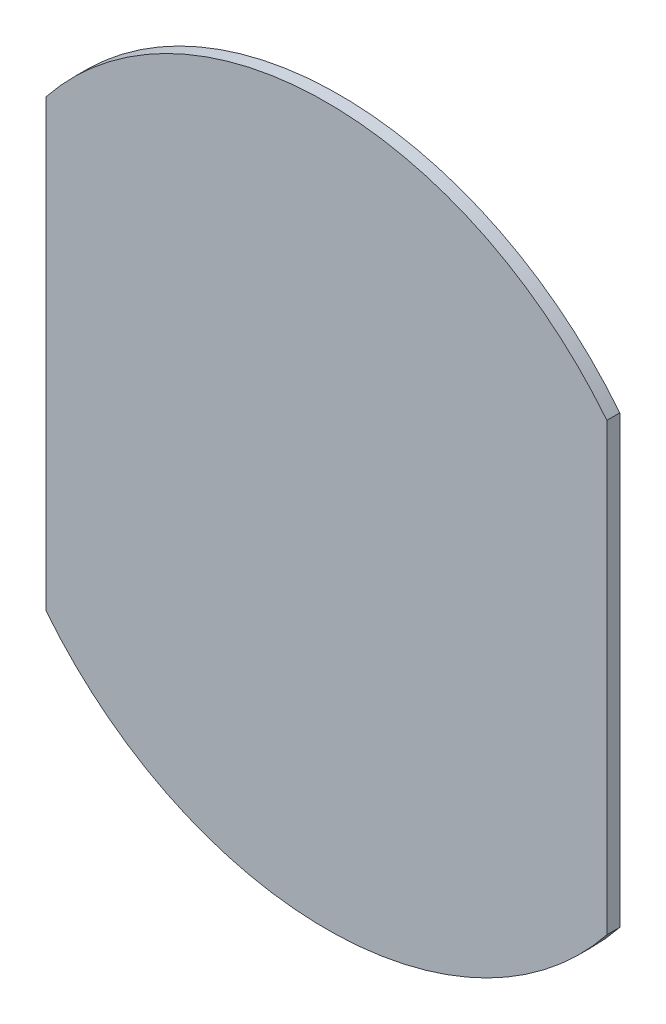
SolidWorks part; units mm, degrees
ref_plane "Přední rovina" through (0, 0, 0) normal (0, 0, 1) x (1, 0, 0)
ref_plane "Horní rovina" through (0, 0, 0) normal (0, 1, 0) x (1, 0, 0)
ref_plane "Pravá rovina" through (0, 0, 0) normal (1, 0, 0) x (0, 0, -1)
sketch "Skica1" plane through (0, 0, 0) normal (0, 0, 1) x (1, 0, 0)
  line L0 (0, 75.9983) -> (0, -86.3937) construction
  line L1 (-44.1124, 16.65) -> (-36.9124, 16.65)
  line L2 (44.1124, 16.65) -> (36.9124, 16.65)
  line L3 (-36.9124, 16.65) -> (-36.9124, -16.65)
  line L4 (36.9124, 16.65) -> (36.9124, -16.65)
  line L5 (-36.9124, -16.65) -> (-44.1124, -16.65)
  line L6 (36.9124, -16.65) -> (44.1124, -16.65)
  line L7 (-47.15, 0) -> (47.15, 0) construction
  arc A0 (-44.1124, -16.65) -> (44.1124, -16.65) centre (0, 0) ccw
  arc A1 (44.1124, 16.65) -> (-44.1124, 16.65) centre (0, 0) ccw
  point P1 (0, -24.75)
  dimension "D1" = 47.15
  dimension "D2" = 7.2
  dimension "D3" = 33.3
extrude "Přidat vysunutím1" add sketch "Skica1" along normal blind 1.7
sketch "Skica2" plane through (0, 0, 0) normal (0, 0, -1) x (-1, 0, 0)
  line L0 (0, 12.2) -> (0, -12.6904) construction
  line L1 (-36.9124, 42.4853) -> (-48.7999, 42.4853)
  line L2 (-36.9124, 42.4853) -> (-36.9124, -45.5506)
  line L3 (-36.9124, -45.5506) -> (-48.7999, -45.5506)
  line L4 (-48.7999, 42.4853) -> (-48.7999, -45.5506)
  line L5 (48.7999, 42.4853) -> (48.7999, -45.5506)
  line L6 (36.9124, -45.5506) -> (48.7999, -45.5506)
  line L7 (36.9124, 42.4853) -> (36.9124, -45.5506)
  line L8 (36.9124, 42.4853) -> (48.7999, 42.4853)
extrude "Odebrat vysunutím1" cut sketch "Skica2" against normal blind 10
